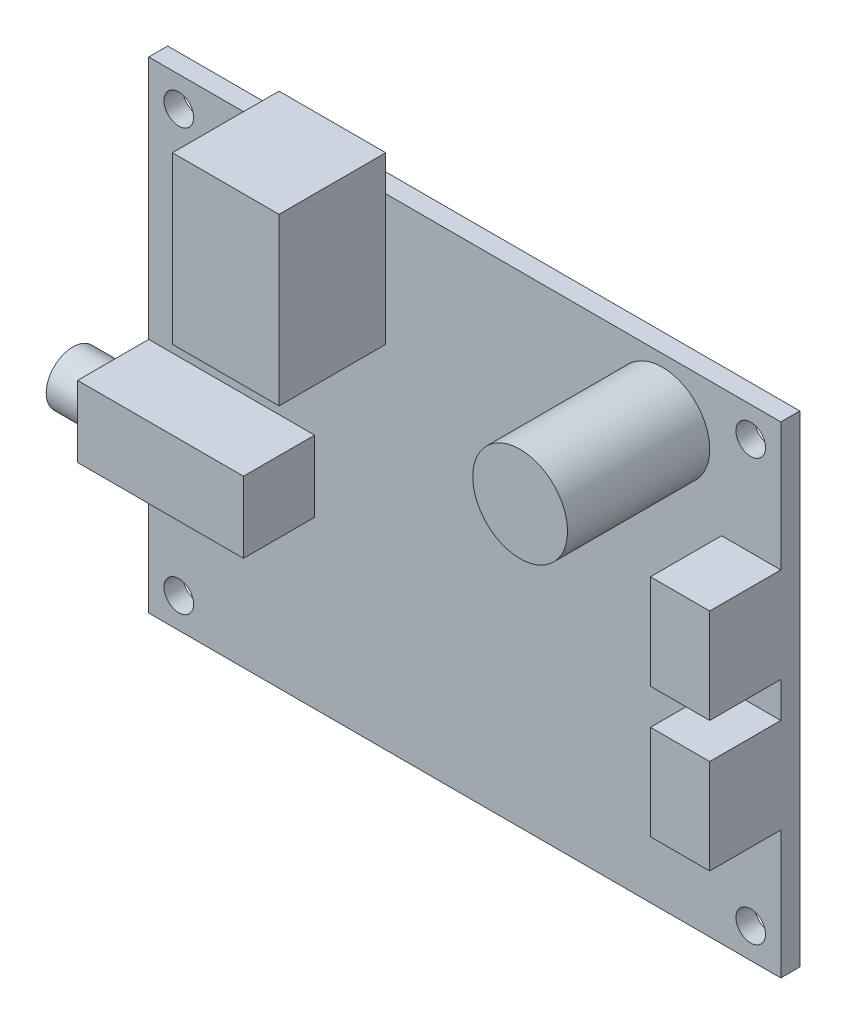
SolidWorks part; units mm, degrees
ref_plane "Plan de face" through (0, 0, 0) normal (0, 0, 1) x (1, 0, 0)
ref_plane "Plan de dessus" through (0, 0, 0) normal (0, 1, 0) x (1, 0, 0)
ref_plane "Plan de droite" through (0, 0, 0) normal (1, 0, 0) x (0, 0, -1)
sketch "Esquisse1" plane through (0, 0, 0) normal (0, 0, 1) x (1, 0, 0)
  line L0 (-24.13, 17.78) -> (24.13, -17.78) construction
  line L1 (-26.67, 20.32) -> (26.67, 20.32)
  line L2 (-26.67, 20.32) -> (-26.67, -20.32)
  line L3 (-26.67, -20.32) -> (26.67, -20.32)
  line L4 (26.67, 20.32) -> (26.67, -20.32)
  circle A0 centre (-24.13, 17.78) radius 1.25
  circle A1 centre (24.13, -17.78) radius 1.25
  circle A2 centre (24.13, 17.78) radius 1.25
  circle A3 centre (-24.13, -17.78) radius 1.25
  point P12 (0, 0)
  point P13 (0, -20.32)
  point P14 (-26.67, 0)
  point P15 (27.2969, -25.1586)
  point P17 (26.67, -20.32)
  dimension "D3" = 2.5
  dimension "D1" = 53.34
  dimension "D2" = 40.64
  dimension "D4" = 48.26
  dimension "D5" = 35.56
extrude "Boss.-Extru.1" add sketch "Esquisse1" along normal blind 1.6
sketch "Esquisse2" plane through (0, 0, 1.6) normal (0, 0, 1) x (1, 0, 0)
  line L0 (-26.67, 20.32) -> (-26.67, -20.32) construction
  line L1 (-26.67, -0.32) -> (-12.67, -0.32)
  line L2 (-26.67, -0.32) -> (-26.67, -6.32)
  line L3 (-26.67, -6.32) -> (-12.67, -6.32)
  line L4 (-12.67, -0.32) -> (-12.67, -6.32)
  line L5 (-26.67, -20.32) -> (26.67, -20.32) construction
  line L6 (26.67, -20.32) -> (26.67, 20.32) construction
  line L7 (26.67, 9.5) -> (21.67, 9.5)
  line L8 (26.67, 9.5) -> (26.67, 1.5)
  line L9 (26.67, 1.5) -> (21.67, 1.5)
  line L10 (21.67, 9.5) -> (21.67, 1.5)
  line L11 (21.67, 1.5) -> (21.67, -1.5) construction
  line L12 (26.67, -9.5) -> (21.67, -9.5)
  line L13 (26.67, -9.5) -> (26.67, -1.5)
  line L14 (26.67, -1.5) -> (21.67, -1.5)
  line L15 (21.67, -9.5) -> (21.67, -1.5)
  point P18 (26.67, 0)
  point P19 (21.67, 0)
  dimension "D1" = 14
  dimension "D2" = 6
  dimension "D3" = 14
  dimension "D4" = 5
  dimension "D5" = 8
  dimension "D6" = 3
extrude "Boss.-Extru.2" add sketch "Esquisse2" along normal blind 6
sketch "Esquisse3" plane through (-26.67, 0, 0) normal (-1, 0, 0) x (0, 0, 1)
  line L0 (7.6, -6.32) -> (1.6, -6.32) construction
  line L1 (7.6, -0.32) -> (7.6, -6.32) construction
  circle A0 centre (4.6, -3.32) radius 2.25
  point P2 (0, 0)
  point P5 (4.6, -6.32)
  point P6 (0, 0)
  point P9 (7.6, -3.32)
  dimension "D1" = 4.5
extrude "Boss.-Extru.3" add sketch "Esquisse3" along normal blind 3.4
sketch "Esquisse4" plane through (0, 0, 1.6) normal (0, 0, 1) x (1, 0, 0)
  line L0 (26.67, 20.32) -> (-26.67, 20.32) construction
  line L1 (-15.67, 23.32) -> (-6.67, 23.32)
  line L2 (-15.67, 23.32) -> (-15.67, 9.32)
  line L3 (-15.67, 9.32) -> (-6.67, 9.32)
  line L4 (-6.67, 23.32) -> (-6.67, 9.32)
  line L5 (-26.67, 20.32) -> (-26.67, -0.32) construction
  dimension "D1" = 3
  dimension "D2" = 14
  dimension "D3" = 11
  dimension "D4" = 9
extrude "Boss.-Extru.4" add sketch "Esquisse4" along normal blind 9
sketch "Esquisse5" plane through (0, 0, 1.6) normal (0, 0, 1) x (1, 0, 0)
  line L0 (26.67, 20.32) -> (-6.67, 20.32) construction
  line L1 (26.67, 9.5) -> (26.67, 20.32) construction
  circle A0 centre (16.67, 15.32) radius 4
  dimension "D1" = 8
  dimension "D2" = 5
  dimension "D3" = 10
extrude "Boss.-Extru.5" add sketch "Esquisse5" along normal blind 12
